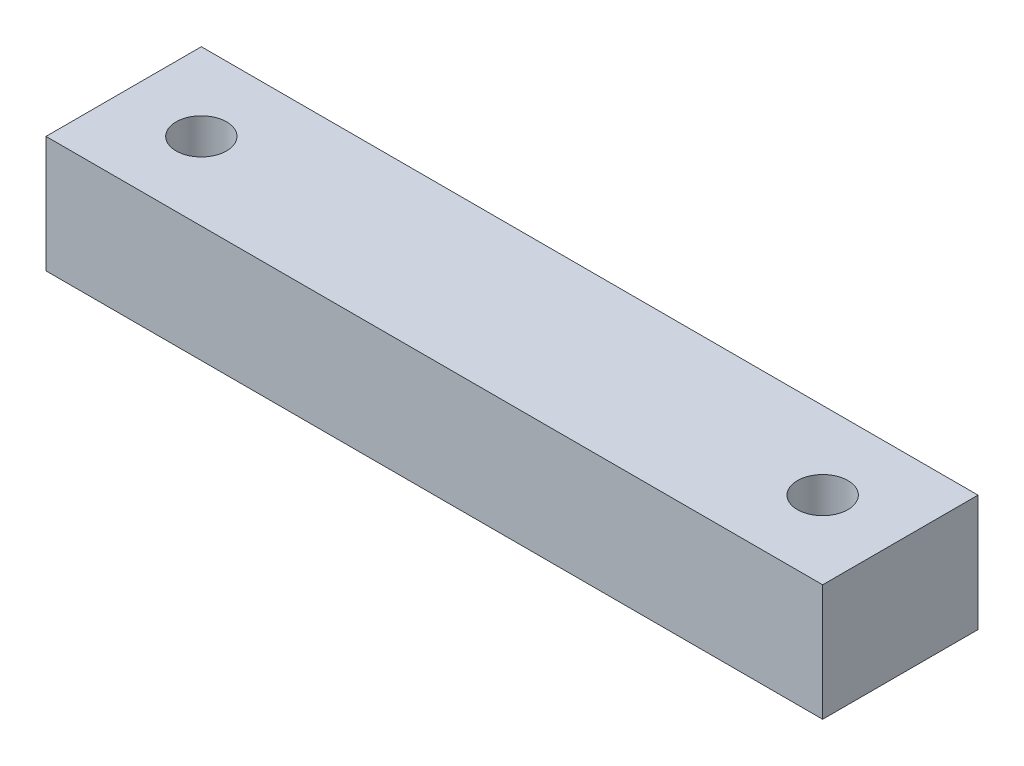
SolidWorks part; units mm, degrees
material "Maple"
ref_plane "Спереди" through (0, 0, 0) normal (0, 0, 1) x (1, 0, 0)
ref_plane "Сверху" through (0, 0, 0) normal (0, 1, 0) x (1, 0, 0)
ref_plane "Справа" through (0, 0, 0) normal (1, 0, 0) x (0, 0, -1)
sketch "Sketch1" plane through (0, 0, 0) normal (0, 1, 0) x (1, 0, 0)
  line L1 (0, 0) -> (100, 0)
  line L2 (0, 0) -> (0, 20)
  line L3 (0, 20) -> (100, 20)
  line L4 (100, 0) -> (100, 20)
  dimension "D1" = 100
  dimension "D2" = 20
extrude "Boss-Extrude1" add sketch "Sketch1" along normal blind 15
sketch "Sketch2" plane through (0, 0, 0) normal (0, -1, 0) x (1, 0, 0)
  line L0 (0, -20) -> (0, 0) construction
  line L1 (0, 0) -> (100, 0) construction
  circle A0 centre (10, -10) radius 7.5
  circle A1 centre (90, -10) radius 7.5
  dimension "D1" = 80
  dimension "D2" = 10
  dimension "D3" = 10
  dimension "D4" = 15
extrude "Cut-Extrude1" cut sketch "Sketch2" against normal blind 6
sketch "Sketch3" plane through (0, 6, 0) normal (0, -1, 0) x (1, 0, 0)
  circle A0 centre (10, -10) radius 3.25
  circle A1 centre (90, -10) radius 3.25
  dimension "D1" = 6.5
extrude "Cut-Extrude2" cut sketch "Sketch3" against normal through all
